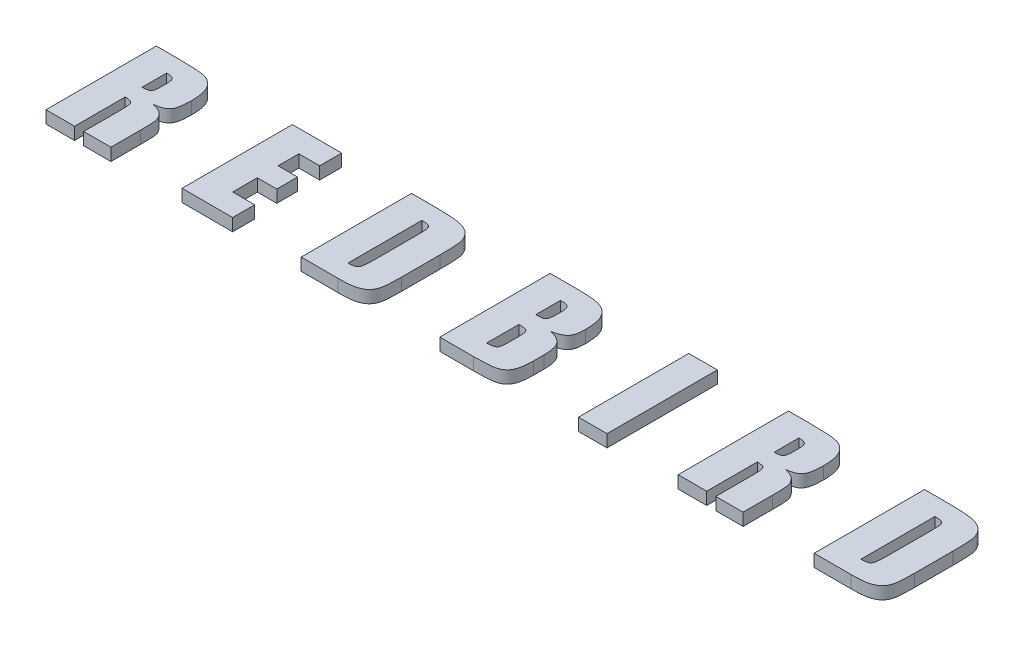
SolidWorks part; units mm, degrees
ref_plane "Front Plane" through (0, 0, 0) normal (0, 0, 1) x (1, 0, 0)
ref_plane "Top Plane" through (0, 0, 0) normal (0, 1, 0) x (1, 0, 0)
ref_plane "Right Plane" through (0, 0, 0) normal (1, 0, 0) x (0, 0, -1)
sketch "Sketch1" plane through (0, 0, 0) normal (0, 1, 0) x (1, 0, 0)
  line L0 (-83.3067, 0) -> (83.3067, 0) construction
  text T0 "REDBIRD" font "Impact" height 17.8
  point P4 (0, 0)
  point P5 (0, 0)
extrude "Boss-Extrude1" add sketch "Sketch1" along normal blind 2
